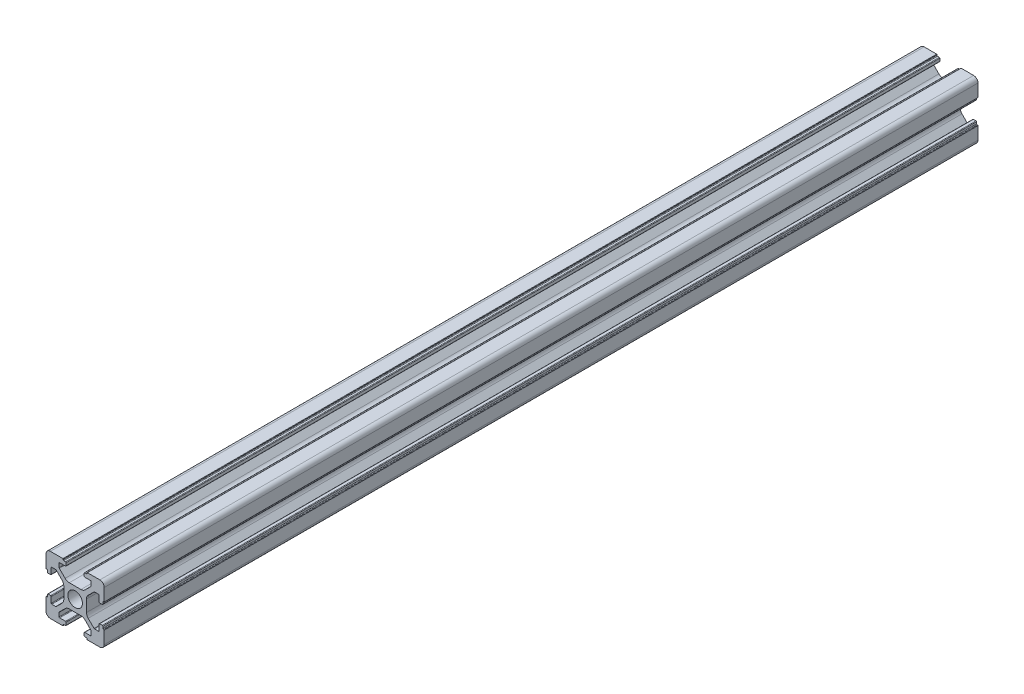
SolidWorks part; units mm, degrees
material "6063-T5"
ref_plane "Front Plane" through (0, 0, 0) normal (0, 0, 1) x (1, 0, 0)
ref_plane "Top Plane" through (0, 0, 0) normal (0, 1, 0) x (1, 0, 0)
ref_plane "Right Plane" through (0, 0, 0) normal (1, 0, 0) x (0, 0, -1)
sketch "Sketch1" plane through (0, 0, 0) normal (0, 0, -1) x (1, 0, 0)
  line L0 (1.5, 0) -> (5.8, 0)
  line L1 (20, 1.5) -> (20, 5.8)
  line L2 (18.5, 20) -> (14.2, 20)
  line L3 (0, 18.5) -> (0, 14.2)
  line L4 (14.2, 0) -> (18.5, 0)
  line L5 (13.3, 18.2) -> (15.3, 18.2)
  line L6 (20, 14.2) -> (20, 18.5)
  line L7 (0, 5.8) -> (0, 1.5)
  line L8 (6.7, 18.2) -> (4.7, 18.2)
  line L9 (1.8, 13.3) -> (1.8, 15.3)
  line L10 (19.3, 13.1) -> (18.4, 13.1)
  line L11 (19.3, 6.9) -> (18.4, 6.9)
  line L12 (6.9, 19.3) -> (6.9, 18.4)
  line L13 (13.1, 19.3) -> (13.1, 18.4)
  line L14 (0.7, 13.1) -> (1.6, 13.1)
  line L15 (0.7, 6.9) -> (1.6, 6.9)
  line L16 (13.4251, 14.4858) -> (15.4121, 16.4728)
  line L17 (14.4858, 13.4251) -> (16.4728, 15.4121)
  line L18 (14.4858, 6.5749) -> (16.4728, 4.5879)
  line L19 (13.4251, 5.5142) -> (15.4121, 3.5272)
  line L20 (6.5749, 5.5142) -> (4.5879, 3.5272)
  line L21 (5.5142, 6.5749) -> (3.5272, 4.5879)
  line L22 (5.5142, 13.4251) -> (3.5272, 15.4121)
  line L23 (6.5749, 14.4858) -> (4.5879, 16.4728)
  line L24 (6.9, 0.7) -> (6.9, 1.6)
  line L25 (13.1, 0.7) -> (13.1, 1.6)
  line L26 (5.8, 20) -> (1.5, 20)
  line L27 (1.8, 6.7) -> (1.8, 4.7)
  line L28 (6.7, 1.8) -> (4.7, 1.8)
  line L29 (13.3, 1.8) -> (15.3, 1.8)
  line L30 (18.2, 13.3) -> (18.2, 15.3)
  line L31 (18.2, 6.7) -> (18.2, 4.7)
  line L32 (2, 4.5) -> (3.3151, 4.5)
  line L33 (2, 15.5) -> (3.3151, 15.5)
  line L34 (4.5, 18) -> (4.5, 16.6849)
  line L35 (15.5, 18) -> (15.5, 16.6849)
  line L36 (18, 15.5) -> (16.6849, 15.5)
  line L37 (4.5, 2) -> (4.5, 3.3151)
  line L38 (15.5, 2) -> (15.5, 3.3151)
  line L39 (18, 4.5) -> (16.6849, 4.5)
  line L40 (7.9891, 13.9) -> (12.0109, 13.9)
  line L41 (7.9891, 6.1) -> (12.0109, 6.1)
  line L42 (13.9, 12.0109) -> (13.9, 7.9891)
  line L43 (6.1, 12.0109) -> (6.1, 7.9891)
  line L44 (19.5, 6.7) -> (19.5, 6.1)
  line L45 (5.9, 19.9) -> (5.9, 19.7)
  line L46 (6.1, 19.5) -> (6.7, 19.5)
  line L47 (14.1, 19.9) -> (14.1, 19.7)
  line L48 (13.9, 19.5) -> (13.3, 19.5)
  line L49 (0.1, 14.1) -> (0.3, 14.1)
  line L50 (0.5, 13.9) -> (0.5, 13.3)
  line L51 (0.1, 5.9) -> (0.3, 5.9)
  line L52 (0.5, 6.1) -> (0.5, 6.7)
  line L53 (19.9, 14.1) -> (19.7, 14.1)
  line L54 (19.5, 13.9) -> (19.5, 13.3)
  line L55 (19.7, 5.9) -> (19.9, 5.9)
  line L56 (14.1, 0.1) -> (14.1, 0.3)
  line L57 (13.9, 0.5) -> (13.3, 0.5)
  line L58 (6.7, 0.5) -> (6.1, 0.5)
  line L59 (5.9, 0.3) -> (5.9, 0.1)
  circle A0 centre (10, 10) radius 2.5
  arc A1 (18.5, 0) -> (20, 1.5) centre (18.5, 1.5) ccw
  arc A2 (1.5, 0) -> (0, 1.5) centre (1.5, 1.5) cw
  arc A3 (20, 18.5) -> (18.5, 20) centre (18.5, 18.5) ccw
  arc A4 (1.5, 20) -> (0, 18.5) centre (1.5, 18.5) ccw
  arc A5 (12.0109, 6.1) -> (13.4251, 5.5142) centre (12.0109, 4.1) cw
  arc A6 (13.9, 7.9891) -> (14.4858, 6.5749) centre (15.9, 7.9891) ccw
  arc A7 (13.9, 12.0109) -> (14.4858, 13.4251) centre (15.9, 12.0109) cw
  arc A8 (12.0109, 13.9) -> (13.4251, 14.4858) centre (12.0109, 15.9) ccw
  arc A9 (7.9891, 13.9) -> (6.5749, 14.4858) centre (7.9891, 15.9) cw
  arc A10 (6.1, 7.9891) -> (5.5142, 6.5749) centre (4.1, 7.9891) cw
  arc A11 (6.1, 12.0109) -> (5.5142, 13.4251) centre (4.1, 12.0109) ccw
  arc A12 (13.1, 1.6) -> (13.3, 1.8) centre (13.3, 1.6) cw
  arc A13 (6.9, 1.6) -> (6.7, 1.8) centre (6.7, 1.6) ccw
  arc A14 (6.1, 0.5) -> (5.9, 0.3) centre (6.1, 0.3) ccw
  arc A15 (6.7, 0.5) -> (6.9, 0.7) centre (6.7, 0.7) ccw
  arc A16 (1.6, 6.9) -> (1.8, 6.7) centre (1.6, 6.7) cw
  arc A17 (0.5, 6.7) -> (0.7, 6.9) centre (0.7, 6.7) cw
  arc A18 (0.5, 13.3) -> (0.7, 13.1) centre (0.7, 13.3) ccw
  arc A19 (1.6, 13.1) -> (1.8, 13.3) centre (1.6, 13.3) ccw
  arc A20 (6.7, 19.5) -> (6.9, 19.3) centre (6.7, 19.3) cw
  arc A21 (6.9, 18.4) -> (6.7, 18.2) centre (6.7, 18.4) cw
  arc A22 (13.1, 18.4) -> (13.3, 18.2) centre (13.3, 18.4) ccw
  arc A23 (13.3, 19.5) -> (13.1, 19.3) centre (13.3, 19.3) ccw
  arc A24 (18.4, 13.1) -> (18.2, 13.3) centre (18.4, 13.3) cw
  arc A25 (19.5, 13.3) -> (19.3, 13.1) centre (19.3, 13.3) cw
  arc A26 (19.5, 6.7) -> (19.3, 6.9) centre (19.3, 6.7) ccw
  arc A27 (14.1, 0.3) -> (13.9, 0.5) centre (13.9, 0.3) ccw
  arc A28 (19.5, 6.1) -> (19.7, 5.9) centre (19.7, 6.1) ccw
  arc A29 (5.9, 19.7) -> (6.1, 19.5) centre (6.1, 19.7) ccw
  arc A30 (14.1, 19.7) -> (13.9, 19.5) centre (13.9, 19.7) cw
  arc A31 (19.7, 14.1) -> (19.5, 13.9) centre (19.7, 13.9) ccw
  arc A32 (13.3, 0.5) -> (13.1, 0.7) centre (13.3, 0.7) cw
  arc A33 (0.3, 14.1) -> (0.5, 13.9) centre (0.3, 13.9) cw
  arc A34 (0.3, 5.9) -> (0.5, 6.1) centre (0.3, 6.1) ccw
  arc A35 (0, 5.8) -> (0.1, 5.9) centre (0.1, 5.8) cw
  arc A36 (5.9, 0.1) -> (5.8, 0) centre (5.8, 0.1) cw
  arc A37 (14.1, 0.1) -> (14.2, 0) centre (14.2, 0.1) ccw
  arc A38 (19.9, 5.9) -> (20, 5.8) centre (19.9, 5.8) cw
  arc A39 (20, 14.2) -> (19.9, 14.1) centre (19.9, 14.2) cw
  arc A40 (14.2, 20) -> (14.1, 19.9) centre (14.2, 19.9) ccw
  arc A41 (5.8, 20) -> (5.9, 19.9) centre (5.8, 19.9) cw
  arc A42 (0, 14.2) -> (0.1, 14.1) centre (0.1, 14.2) ccw
  arc A43 (18.4, 6.9) -> (18.2, 6.7) centre (18.4, 6.7) ccw
  arc A44 (1.8, 15.3) -> (2, 15.5) centre (2, 15.3) cw
  arc A45 (1.8, 4.7) -> (2, 4.5) centre (2, 4.7) ccw
  arc A46 (4.7, 1.8) -> (4.5, 2) centre (4.7, 2) cw
  arc A47 (15.3, 1.8) -> (15.5, 2) centre (15.3, 2) ccw
  arc A48 (18.2, 4.7) -> (18, 4.5) centre (18, 4.7) cw
  arc A49 (18.2, 15.3) -> (18, 15.5) centre (18, 15.3) ccw
  arc A50 (15.3, 18.2) -> (15.5, 18) centre (15.3, 18) cw
  arc A51 (4.7, 18.2) -> (4.5, 18) centre (4.7, 18) ccw
  arc A52 (7.9891, 6.1) -> (6.5749, 5.5142) centre (7.9891, 4.1) ccw
  arc A53 (3.3151, 15.5) -> (3.5272, 15.4121) centre (3.3151, 15.2) cw
  arc A54 (4.5, 16.6849) -> (4.5879, 16.4728) centre (4.8, 16.6849) ccw
  arc A55 (15.5, 16.6849) -> (15.4121, 16.4728) centre (15.2, 16.6849) cw
  arc A56 (16.6849, 15.5) -> (16.4728, 15.4121) centre (16.6849, 15.2) ccw
  arc A57 (16.6849, 4.5) -> (16.4728, 4.5879) centre (16.6849, 4.8) cw
  arc A58 (15.5, 3.3151) -> (15.4121, 3.5272) centre (15.2, 3.3151) ccw
  arc A59 (4.5, 3.3151) -> (4.5879, 3.5272) centre (4.8, 3.3151) cw
  arc A60 (3.3151, 4.5) -> (3.5272, 4.5879) centre (3.3151, 4.8) ccw
  point P67 (0, 0)
  point P125 (14.1, 19.5)
extrude "Boss-Extrude1" add sketch "Sketch1" along normal blind 300 contours L23 A54 L34 A51 L8 A21 L12 A20 L46 A29 L45 A41 L26 A4 L3 A42 L49 A33 L50 A18 L14 A19 L9 A44 L33 A53 L22 A11 L43 A10 L21 A60 L32 A45 L27 A16 L15 A17 L52 A34 L51 A35 L7 A2 L0 A36 L59 A14 L58 A15 L24 A13 L28 A46 L37 A59 L20 A52 L41 A5 L19 A58 L38 A47 L29 A12 L25 A32 L57 A27 L56 A37 L4 A1 L1 A38 L55 A28 L44 A26 L11 A43 L31 A48 L39 A57 L18 A6 L42 A7 L17 A56 L36 A49 L30 A24 L10 A25 L54 A31 L53 A39 L6 A3 L2 A40 L47 A30 L48 A23 L13 A22 L5 A50 L35 A55 L16 A8 L40 A9 | A0
